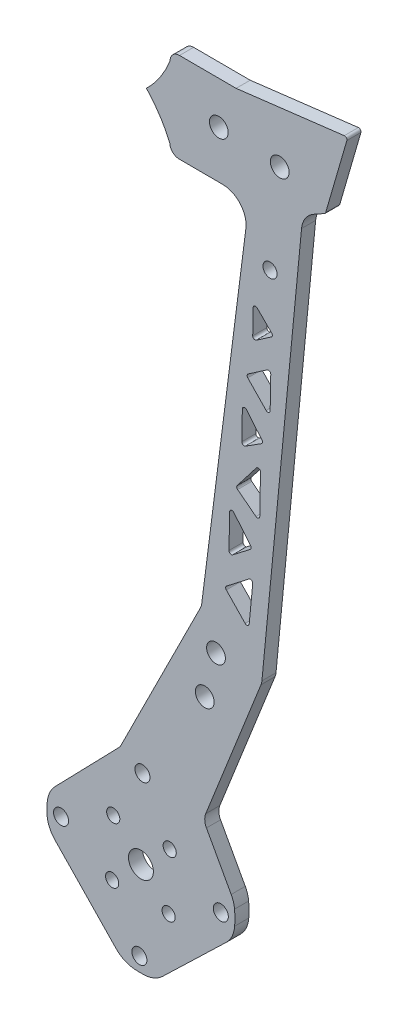
SolidWorks part; units mm, degrees
ref_plane "前视基准面" through (0, 0, 0) normal (0, 0, 1) x (1, 0, 0)
ref_plane "上视基准面" through (0, 0, 0) normal (0, 1, 0) x (1, 0, 0)
ref_plane "右视基准面" through (0, 0, 0) normal (1, 0, 0) x (0, 0, -1)
sketch "草图1" plane through (0, 0, 0) normal (0, 0, 1) x (1, 0, 0)
  line L0 (180.8764, 205.2281) -> (168.8312, 205.2681)
  line L4 (168.7408, 186.1346) -> (178.0275, 186.0907)
  line L24 (197.3476, 190.2445) -> (199.7041, 191.5595)
  line L25 (199.9406, 191.8567) -> (204.4479, 207.3839)
  line L26 (203.9076, 208.0197) -> (180.8764, 205.2281)
  line L28 (182.9639, 180.4594) -> (173.5642, 106.6084)
  line L29 (173.271, 105.6445) -> (156.4018, 71.9374)
  line L30 (155.8716, 71.1904) -> (142.3567, 57.2689)
  line L31 (142.3051, 47.4219) -> (155.3314, 33.8911)
  line L32 (165.2178, 33.7032) -> (178.7486, 46.7296)
  line L33 (179.8317, 56.1186) -> (174.5666, 65.7464)
  line L34 (174.4102, 68.2923) -> (186.1733, 97.9356)
  line L35 (186.371, 98.7546) -> (194.8071, 186.3576)
  line L38 (188.4402, 163.9096) -> (185.3676, 166.9843)
  line L40 (184.514, 166.6404) -> (184.4141, 161.3833)
  line L42 (185.1974, 160.9619) -> (188.3699, 163.1442)
  line L44 (187.4728, 156.6328) -> (183.4408, 153.8591)
  line L46 (183.3639, 153.1004) -> (187.2663, 149.0469)
  line L48 (188.1264, 149.3842) -> (188.2561, 156.2113)
  line L50 (182.2057, 146.7907) -> (182.0898, 140.6902)
  line L52 (182.8578, 140.2587) -> (186.2606, 142.4205)
  line L54 (186.3764, 143.1629) -> (183.0895, 147.1015)
  line L56 (185.1716, 137.4029) -> (181.1079, 132.131)
  line L58 (181.1987, 131.4297) -> (185.105, 128.4187)
  line L60 (185.9102, 128.8052) -> (186.0675, 137.0881)
  line L62 (183.9844, 122.4836) -> (180.3838, 126.7982)
  line L64 (179.5, 126.4874) -> (179.3631, 119.2845)
  line L66 (180.1688, 118.8793) -> (183.9063, 121.7677)
  line L68 (183.6118, 116.1475) -> (178.8484, 112.4663)
  line L70 (178.7939, 111.7239) -> (182.802, 107.5606)
  line L72 (183.6599, 107.8595) -> (184.4153, 115.7039)
  circle A1 centre (160.9436, 69.0159) radius 1.6
  circle A3 centre (177.6177, 51.696) radius 1.6
  circle A5 centre (160.2979, 35.022) radius 1.6
  circle A7 centre (176.6003, 99.006) radius 2
  circle A9 centre (174.2077, 89.7447) radius 2
  circle A11 centre (188.1008, 175.3409) radius 1.5
  arc A13 (168.8312, 205.2681) -> (166.8218, 203.2776) centre (168.8218, 203.2682) ccw
  arc A16 (166.7503, 188.144) -> (168.7408, 186.1346) centre (168.7503, 188.1345) ccw
  arc A34 (199.7041, 191.5595) -> (199.9406, 191.8567) centre (199.4605, 191.9961) ccw
  arc A35 (204.4479, 207.3839) -> (203.9076, 208.0197) centre (203.9678, 207.5233) ccw
  arc A37 (173.271, 105.6445) -> (173.5642, 106.6084) centre (170.5883, 106.9872) ccw
  arc A38 (155.8716, 71.1904) -> (156.4018, 71.9374) centre (153.719, 73.2801) ccw
  arc A39 (142.3567, 57.2689) -> (140.6793, 53.5485) centre (146.6617, 53.0896) ccw
  arc A40 (140.6793, 53.5485) -> (140.6304, 51.3965) centre (160.6207, 52.0189) ccw
  arc A41 (140.6304, 51.3965) -> (142.3051, 47.4219) centre (146.6275, 51.5832) ccw
  arc A42 (155.3314, 33.8911) -> (159.2395, 32.0667) centre (159.6539, 38.0523) ccw
  arc A43 (159.2395, 32.0667) -> (161.2432, 32.0286) centre (160.6207, 52.0189) ccw
  arc A44 (161.2432, 32.0286) -> (165.2178, 33.7032) centre (161.0565, 38.0257) ccw
  arc A45 (178.7486, 46.7296) -> (180.573, 50.6377) centre (174.5873, 51.0521) ccw
  arc A46 (180.573, 50.6377) -> (180.5446, 53.763) centre (160.6207, 52.0189) ccw
  arc A47 (180.5446, 53.763) -> (179.8317, 56.1186) centre (174.5674, 53.2398) ccw
  arc A48 (174.4102, 68.2923) -> (174.5666, 65.7464) centre (177.1987, 67.1858) ccw
  arc A49 (186.1733, 97.9356) -> (186.371, 98.7546) centre (183.3848, 99.0422) ccw
  arc A50 (197.3476, 190.2445) -> (194.8071, 186.3576) centre (199.784, 185.8783) ccw
  arc A51 (178.0275, 186.0907) -> (182.9639, 180.4594) centre (178.0039, 181.0907) cw
  circle A53 centre (193.305, 194.2503) radius 2
  circle A54 centre (177.1987, 196.2267) radius 2
  arc A56 (185.3676, 166.9843) -> (184.514, 166.6404) centre (185.0139, 166.6309) ccw
  arc A58 (184.4141, 161.3833) -> (185.1974, 160.9619) centre (184.914, 161.3738) ccw
  arc A60 (188.3699, 163.1442) -> (188.4402, 163.9096) centre (188.0865, 163.5562) ccw
  arc A62 (183.4408, 153.8591) -> (183.3639, 153.1004) centre (183.7241, 153.4472) ccw
  arc A64 (188.2561, 156.2113) -> (187.4728, 156.6328) centre (187.7562, 156.2208) ccw
  arc A66 (187.2663, 149.0469) -> (188.1264, 149.3842) centre (187.6265, 149.3937) ccw
  arc A68 (183.0895, 147.1015) -> (182.2057, 146.7907) centre (182.7056, 146.7812) ccw
  arc A70 (182.0898, 140.6902) -> (182.8578, 140.2587) centre (182.5897, 140.6807) ccw
  arc A72 (186.2606, 142.4205) -> (186.3764, 143.1629) centre (185.9925, 142.8425) ccw
  arc A74 (181.1079, 132.131) -> (181.1987, 131.4297) centre (181.504, 131.8257) ccw
  arc A76 (186.0675, 137.0881) -> (185.1716, 137.4029) centre (185.5676, 137.0976) ccw
  arc A78 (185.105, 128.4187) -> (185.9102, 128.8052) centre (185.4103, 128.8147) ccw
  arc A80 (180.3838, 126.7982) -> (179.5, 126.4874) centre (179.9999, 126.4779) ccw
  arc A82 (179.3631, 119.2845) -> (180.1688, 118.8793) centre (179.863, 119.275) ccw
  arc A84 (183.9063, 121.7677) -> (183.9844, 122.4836) centre (183.6005, 122.1633) ccw
  arc A86 (178.8484, 112.4663) -> (178.7939, 111.7239) centre (179.1541, 112.0707) ccw
  arc A88 (184.4153, 115.7039) -> (183.6118, 116.1475) centre (183.9176, 115.7519) ccw
  arc A90 (182.802, 107.5606) -> (183.6599, 107.8595) centre (183.1622, 107.9074) ccw
  circle A92 centre (143.6238, 52.3418) radius 1.6
  circle A94 centre (166.5159, 45.8954) radius 1.4
  circle A96 centre (166.7442, 57.9141) radius 1.4
  circle A98 centre (154.4973, 46.1238) radius 1.4
  circle A100 centre (154.7256, 58.1424) radius 1.4
  circle A102 centre (160.6207, 52.0189) radius 2.65
  spline S1 degree 2 poles (161.7861, 195.7108) (165.1396, 198.942) (166.8218, 203.2776) knots 0 0 0 1 1 1
  spline S2 degree 2 poles (161.7861, 195.7108) (164.9279, 192.3611) (166.7503, 188.144) knots 0 0 0 1 1 1
  dimension "D2" = 5
  dimension "D3" = 4
extrude "凸台-拉伸1" add sketch "草图1" along normal blind 3
sketch "草图2" plane through (0, 0, 3) normal (0, 0, 1) x (1, 0, 0)
  circle A0 centre (193.305, 194.2503) radius 2 construction
  circle A1 centre (193.305, 194.2503) radius 2
extrude "凸台-拉伸2" add sketch "草图2" against normal up to surface (3 mm away) up to face at (181.2038, 122.6229, 0)
sketch "草图3" plane through (0, 0, 3) normal (0, 0, 1) x (1, 0, 0)
  circle A0 centre (190.164, 195.3744) radius 2 construction
  circle A1 centre (190.164, 195.3744) radius 2
extrude "切除-拉伸1" cut sketch "草图3" against normal through all
